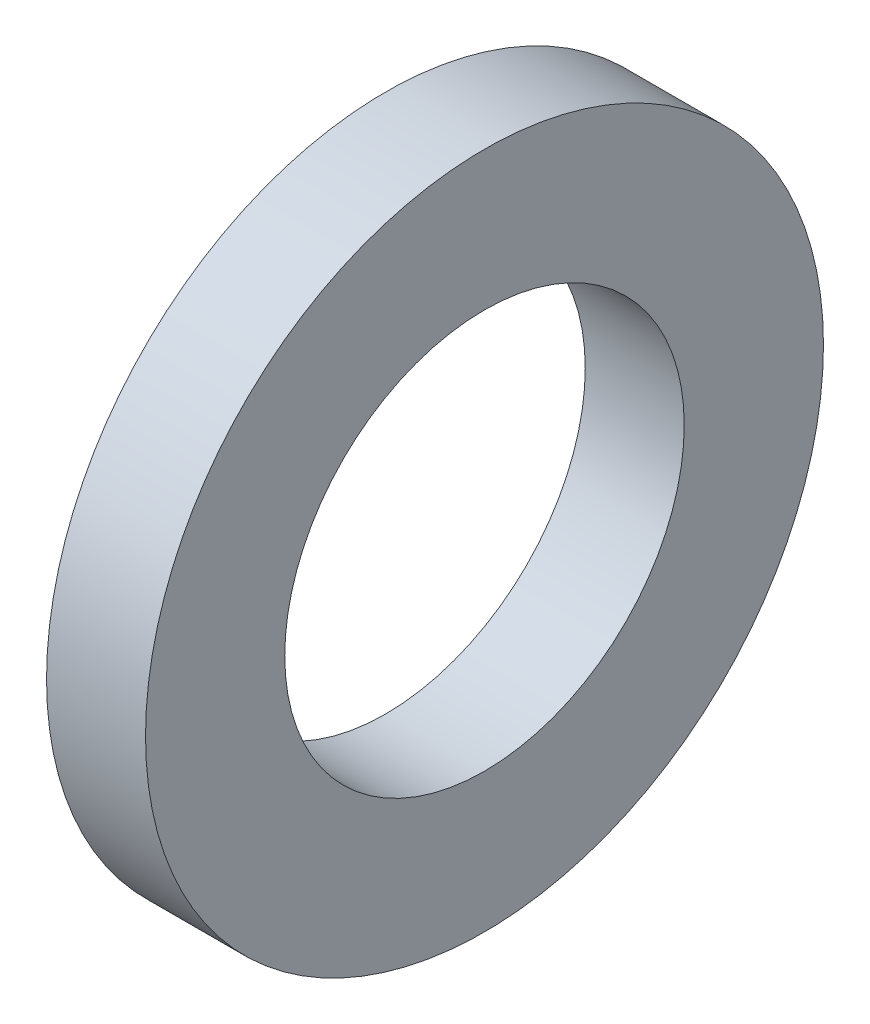
SolidWorks part; units mm, degrees
material "PET"
ref_plane "Front Plane" through (0, 0, 0) normal (0, 0, 1) x (1, 0, 0)
ref_plane "Top Plane" through (0, 0, 0) normal (0, 1, 0) x (1, 0, 0)
ref_plane "Right Plane" through (0, 0, 0) normal (1, 0, 0) x (0, 0, -1)
sketch "Sketch1" plane through (0, 0, 0) normal (1, 0, 0) x (0, 0, -1)
  circle A0 centre (0, 0) radius 5.2387
  circle A1 centre (0, 0) radius 8.89
  dimension "D1" = 10.4775
  dimension "D2" = 17.78
extrude "Boss-Extrude1" add sketch "Sketch1" along normal mid plane 2.5959
